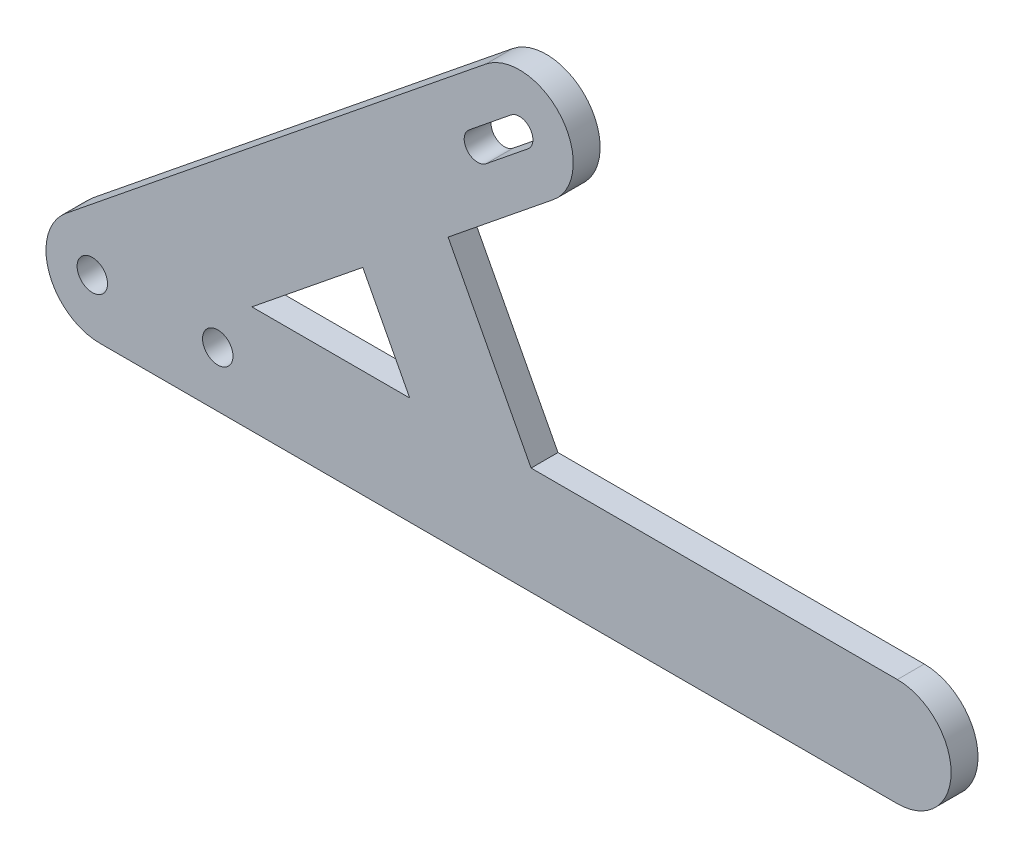
SolidWorks part; units mm, degrees
ref_plane "Plan de face" through (0, 0, 0) normal (0, 0, 1) x (1, 0, 0)
ref_plane "Plan de dessus" through (0, 0, 0) normal (0, 1, 0) x (1, 0, 0)
ref_plane "Plan de droite" through (0, 0, 0) normal (1, 0, 0) x (0, 0, -1)
sketch "Esquisse1" plane through (0, 0, 0) normal (0, 0, 1) x (1, 0, 0)
  line L0 (-44.5, 0) -> (44.5, 0) construction
  line L2 (-44.5, -6) -> (44.5, -6)
  line L3 (-44.5, 0) -> (2.3336, 37.8374) construction
  line L4 (2.3336, 37.8374) -> (-2.3336, 34.0668) construction
  line L5 (3.2762, 36.6706) -> (-1.3909, 32.9)
  line L6 (1.3909, 39.0042) -> (-3.2762, 35.2336)
  line L7 (-48.2706, 4.6671) -> (-1.4371, 42.5046)
  line L8 (-27.526, 6) -> (-9.9119, 6)
  line L9 (0, 0) -> (-13.2236, 25.2686) construction
  line L10 (-27.526, 6) -> (-15.1461, 16.0019)
  line L11 (3.632, 6) -> (-5.6269, 23.6926)
  line L12 (-5.6269, 23.6926) -> (6.1042, 33.1703)
  line L13 (3.632, 6) -> (44.5, 6)
  line L14 (-9.9119, 6) -> (-15.1461, 16.0019)
  arc A7 (-48.2706, 4.6671) -> (-44.5, -6) centre (-44.5, 0) ccw
  arc A8 (44.5, -6) -> (44.5, 6) centre (44.5, 0) ccw
  arc A9 (3.2762, 36.6706) -> (1.3909, 39.0042) centre (2.3336, 37.8374) ccw
  arc A10 (-3.2762, 35.2336) -> (-1.3909, 32.9) centre (-2.3336, 34.0668) ccw
  arc A11 (-48.2706, 4.6671) -> (-44.5, -6) centre (-44.5, 0) ccw
  arc A12 (6.1042, 33.1703) -> (-1.4371, 42.5046) centre (2.3336, 37.8374) ccw
  point P0 (0, 0)
  point P3 (0, 35.9521)
  point P17 (0, 0)
  point P25 (0, 35.9521)
  point P31 (-21.0832, 18.9187)
  point P38 (-6.6118, 12.6343)
  dimension "D16" = 3
  dimension "D17" = 6
  dimension "D21" = 17
extrude "Boss.-Extru.1" add sketch "Esquisse1" along normal blind 3 contours L12 A12 L7 A7 L2 A8 L13 L11 L14 L8 L10 A10 L6 A9 L5
hole_wizard "Dégagement M31" positions "Esquisse3" profile "Esquisse2" hole size "M3" standard "ISO"
sketch "Esquisse3" plane through (0, 0, 3) normal (0, 0, 1) x (1, 0, 0)
  circle A0 centre (-45.3292, 0.1777) radius 1.55 construction
  circle A1 centre (-31.3292, 0.1777) radius 1.25 construction
  point P0 (-45.3292, 0.1777)
  point P1 (-31.3292, 0.1777)
sketch "Esquisse2" plane through (-45.3292, 0.1777, 3) normal (1, 0, 0) x (0, -1, 0)
  line L0 (0, 0) -> (0, 11.0215)
  line L1 (0, 11.0215) -> (1.7, 10)
  line L2 (1.7, 10) -> (1.7, 0)
  line L5 (1.7, 0) -> (0, 0)
  line L10 (0, 11.0215) -> (-1.7, 10) construction
  line L11 (0, -6.35) -> (0, 107.95) construction
  dimension "Diamètre du perçage" = 3.4
  dimension "Profondeur du perçage" = 10
  dimension "Angle de pointe" = 118
